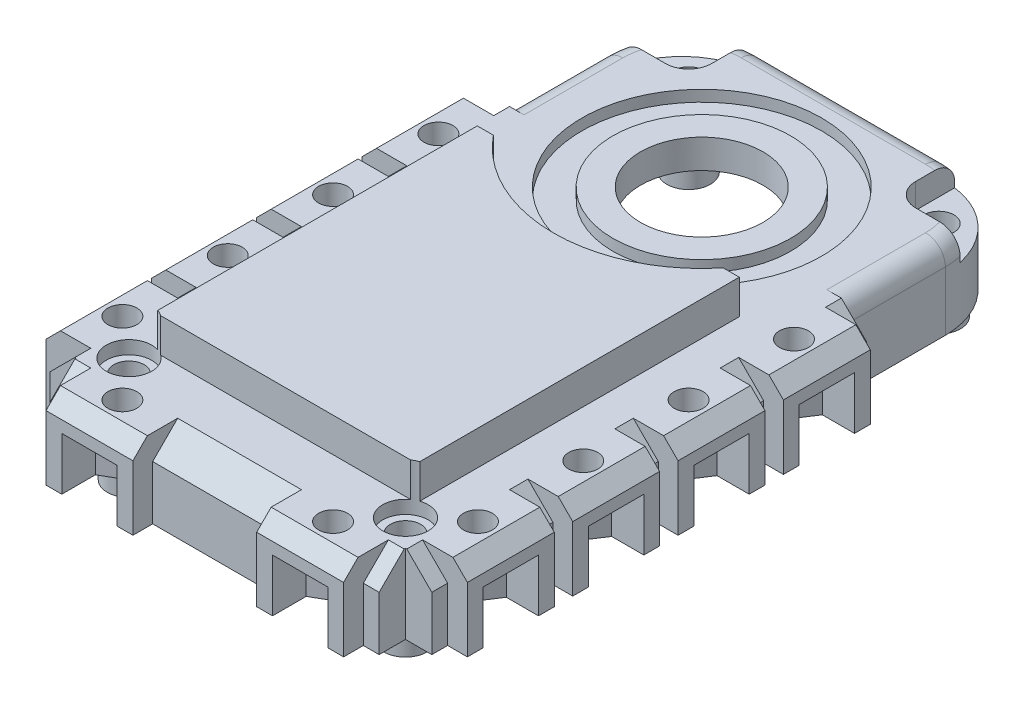
SolidWorks part; units mm, degrees
ref_plane "Front Plane" through (0, 0, 0) normal (0, 0, 1) x (1, 0, 0)
ref_plane "Top Plane" through (0, 0, 0) normal (0, 1, 0) x (1, 0, 0)
ref_plane "Right Plane" through (0, 0, 0) normal (1, 0, 0) x (0, 0, -1)
sketch "Sketch1" plane through (0, 0, 0) normal (0, 1, 0) x (1, 0, 0)
  line L0 (-55, 0) -> (55, 0) construction
  line L1 (-16, -25) -> (16, -25)
  line L2 (-16, -25) -> (-16, 25)
  line L3 (-16, 25) -> (16, 25)
  line L4 (16, -25) -> (16, 25)
  line L5 (0, -55) -> (0, 55) construction
  point P4 (16, 0)
  point P9 (0, 25)
  dimension "D1" = 32
  dimension "D2" = 50
extrude "Boss-Extrude1" add sketch "Sketch1" along normal mid plane 6
sketch "Sketch4" plane through (0, 3, 0) normal (0, 1, 0) x (1, 0, 0)
  line L0 (-13, 19) -> (-13, 11.5)
  line L1 (-13, 11.5) -> (-14.5, 11.5)
  line L2 (-14.5, 11.5) -> (-14.5, 10.3)
  line L3 (-14.5, 10.3) -> (-16, 10.3)
  line L4 (-16, 25) -> (-16, -25)
  line L5 (-16, -25) -> (16, -25)
  line L6 (16, -25) -> (16, 25)
  line L7 (16, 25) -> (-16, 25)
  line L8 (-16, 10.3) -> (-16, 3.7)
  line L9 (-11.3, -25) -> (-4.7, -25)
  line L12 (-16, 3.7) -> (-14.5, 3.7)
  line L13 (-14.5, 3.7) -> (-14.5, 2.3)
  line L14 (-14.5, 2.3) -> (-16, 2.3)
  line L15 (-16, 2.3) -> (-16, -4.3)
  line L16 (-16, -5.7) -> (-16, -12.3)
  line L17 (-16, -4.3) -> (-14.5, -4.3)
  line L19 (-16, -5.7) -> (-14.5, -5.7)
  line L20 (-14.5, -4.3) -> (-14.5, -5.7)
  line L21 (-16, 25) -> (-16, -25) construction
  line L22 (-16, -13.7) -> (-16, -20.3)
  line L23 (-16, -12.3) -> (-14.5, -12.3)
  line L25 (-16, -13.7) -> (-14.5, -13.7)
  line L26 (-14.5, -12.3) -> (-14.5, -13.7)
  line L27 (-16, -20.3) -> (-14.5, -20.3)
  line L28 (-14.5, -20.3) -> (-14.5, -21.5)
  line L29 (-14.5, -21.5) -> (-12.5, -21.5)
  line L30 (-12.5, -21.5) -> (-12.5, -23.5)
  line L31 (-12.5, -23.5) -> (-11.3, -23.5)
  line L32 (-11.3, -23.5) -> (-11.3, -25)
  line L35 (-4.7, -23.5) -> (-4.7, -25)
  line L38 (0, -55) -> (0, 55) construction
  line L41 (-20, 25) -> (-20, -26)
  line L42 (-20, -26) -> (0, -26)
  line L43 (0, -23.5) -> (0, -26)
  line L44 (-4.7, -23.5) -> (0, -23.5)
  line L45 (16, 25) -> (-16, 25) construction
  line L46 (-20, 25) -> (-7, 25)
  arc A0 (-7, 25) -> (-13, 19) centre (-7, 19) ccw
  dimension "D6" = 6
  dimension "D2" = 6.6
  dimension "D3" = 1.2
  dimension "D4" = 1.4
  dimension "D5" = 1.5
  dimension "D7" = 1.5
  dimension "D8" = 4.7
  dimension "D9" = 13
  dimension "D10" = 20
  dimension "D11" = 13.5
  dimension "D12" = 51
  dimension "D1" = 0
extrude "Cut-Extrude1" cut sketch "Sketch4" against normal blind 10
mirror "Mirror1" about plane through (0, 0, 0) normal (1, 0, 0) of "Cut-Extrude1"
sketch "Sketch5" plane through (0, 3, 0) normal (0, 1, 0) x (1, 0, 0)
  line L0 (-16, 10.3) -> (-16, 3.7) construction
  line L1 (-14.5, 3.7) -> (-16, 3.7) construction
  line L2 (-11.3, -25) -> (-4.7, -25) construction
  line L3 (0, -55) -> (0, 55) construction
  circle A0 centre (-13.5, 7) radius 1.1
  circle A1 centre (13.5, 7) radius 1.1
  circle A2 centre (13.5, -1) radius 1.1
  circle A3 centre (13.5, -9) radius 1.1
  circle A4 centre (13.5, -17) radius 1.1
  circle A5 centre (-13.5, -1) radius 1.1
  circle A6 centre (-13.5, -9) radius 1.1
  circle A7 centre (-13.5, -17) radius 1.1
  circle A8 centre (-8, -22.5) radius 1.1
  circle A9 centre (8, -22.5) radius 1.1
  dimension "D3" = 2.2
  dimension "D1" = 2.5
  dimension "D2" = 3.3
  dimension "D6" = 8
  dimension "D7" = 27
  dimension "D8" = 16
  dimension "D9" = 2.5
  dimension "D10" = 8
  dimension "D4" = 2
  dimension "D5" = 4
extrude "Cut-Extrude2" cut sketch "Sketch5" against normal blind 10
chamfer "Chamfer1" distance 1.1 angle 45 10 edges at (8, 3, 25) (16, 3, -7) (16, 3, 1) (16, 3, 9) (16, 3, 17) (-8, 3, 25) (-16, 3, 17) (-16, 3, 9) (-16, 3, 1) (-16, 3, -7)
fillet "Fillet1" radius 1.5 5 edges at (13, 3, -15.25) (11.2426, 3, -23.2426) (0, 3, -25) (-11.2426, 3, -23.2426) (-13, 3, -15.25)
chamfer "Chamfer2" distance 1.9 angle 45 13 edges at (-14.5, 3, -3) (-14.5, 3, 13) (-14.5, 3, 5) (-14.5, 3, -10.9) (14.5, 3, -10.9) (14.5, 3, -3) (14.5, 3, 5) (14.5, 3, 13) (11.9, 3, 23.5) (0, 3, 23.5) (-11.9, 3, 23.5) (14.5, 3, 20.9) (-14.5, 3, 20.9)
sketch "Sketch24" plane through (0, 3, 0) normal (0, 1, 0) x (1, 0, 0)
  line L0 (-7, 25) -> (7, 25) construction
  circle A0 centre (0, 13.5) radius 9.1
  point P2 (0, 0)
  dimension "D1" = 18.2
  dimension "D2" = 11.5
extrude "Cut-Extrude15" cut sketch "Sketch24" against normal blind 0.85
sketch "Sketch8" plane through (0, 3, 0) normal (0, 1, 0) x (1, 0, 0)
  line L0 (0, -3.3) -> (0, 3.3) construction
  line L1 (-7, 25) -> (7, 25) construction
  circle A0 centre (0, 13.5) radius 6.75
  dimension "D1" = 13.5
  dimension "D2" = 11.5
extrude "Boss-Extrude3" add sketch "Sketch8" against normal up to surface (0.85 mm away) up to face at (0, 2.15, -4.4)
ref_plane "Plane1" through (0, 1, 0) normal (0, 1, 0) x (1, 0, 0)
sketch "Sketch12" plane through (0, 1, 0) normal (0, 1, 0) x (1, 0, 0)
  line L1 (-12.2876, 9.1) -> (-14.7124, 9.1)
  line L2 (-14.7124, 9.1) -> (-15.9249, 7) construction
  line L3 (-15.9249, 7) -> (-14.7124, 4.9) construction
  line L4 (-14.7124, 4.9) -> (-12.2876, 4.9)
  line L5 (-12.2876, 4.9) -> (-11.0751, 7)
  line L6 (-11.0751, 7) -> (-12.2876, 9.1)
  line L49 (-14.7124, 9.1) -> (-17.7124, 9.1)
  line L50 (-14.7124, 9.1) -> (-14.7124, 4.9) construction
  line L51 (-14.7124, 4.9) -> (-17.7124, 4.9)
  line L52 (-17.7124, 9.1) -> (-17.7124, 4.9)
  circle A0 centre (-13.5, 7) radius 2.1 construction
  circle A1 centre (-13.5, 7) radius 1.1 construction
  dimension "D1" = 4.2
  dimension "D2" = 3
extrude "Cut-Extrude7" cut sketch "Sketch12" against normal blind 1.5
sketch "Sketch13" plane through (0, -3, 0) normal (0, -1, 0) x (1, 0, 0)
  line L0 (-16, -4.9) -> (-13.4423, -4.9)
  line L1 (-13.4423, -4.9) -> (-12.5474, -6.45)
  line L2 (-16, -9.1) -> (-13.5577, -9.1)
  line L3 (-13.5577, -9.1) -> (-12.579, -7.6015)
  line L4 (-16, -4.9) -> (-16, -9.1)
  line L5 (-16, -4.9) -> (-12.2876, -4.9) construction
  line L6 (-16, -9.1) -> (-16, -4.9) construction
  line L7 (-12.2876, -4.9) -> (-11.0751, -7) construction
  circle A0 centre (-13.5, -7) radius 1.1 construction
  arc A1 (-12.579, -7.6015) -> (-12.5474, -6.45) centre (-13.5, -7) ccw
  point P8 (-16, -7)
extrude "Cut-Extrude8" cut sketch "Sketch13" against normal up to next
pattern_linear "LPattern1" count 4 spacing 8 along (0, 0, 1) of "Cut-Extrude7", "Cut-Extrude8"
sketch "Sketch14" plane through (0, 1, 0) normal (0, 1, 0) x (1, 0, 0)
  line L1 (-8, -24.9249) -> (-5.9, -23.7124) construction
  line L2 (-5.9, -23.7124) -> (-5.9, -21.2876)
  line L3 (-5.9, -21.2876) -> (-8, -20.0751)
  line L4 (-8, -20.0751) -> (-10.1, -21.2876)
  line L5 (-10.1, -21.2876) -> (-10.1, -23.7124)
  line L6 (-10.1, -23.7124) -> (-8, -24.9249) construction
  line L7 (-10.1, -23.7124) -> (-5.9, -23.7124) construction
  line L8 (-10.1, -23.7124) -> (-10.1, -26.7124)
  line L9 (-10.1, -26.7124) -> (-5.9, -26.7124)
  line L10 (-5.9, -23.7124) -> (-5.9, -26.7124)
  circle A0 centre (-8, -22.5) radius 2.1 construction
  circle A1 centre (-8, -22.5) radius 1.1 construction
  dimension "D1" = 4.2
  dimension "D2" = 3
extrude "Cut-Extrude9" cut sketch "Sketch14" against normal blind 1.55
sketch "Sketch15" plane through (0, -3, 0) normal (0, -1, 0) x (1, 0, 0)
  line L0 (-10.1, 25) -> (-5.9, 25)
  line L1 (-5.9, 25) -> (-5.9, 22.4423)
  line L2 (-5.9, 22.4423) -> (-7.45, 21.5474)
  line L3 (-10.1, 25) -> (-10.1, 22.4423)
  line L4 (-10.1, 22.4423) -> (-8.55, 21.5474)
  line L5 (-5.9, 25) -> (-5.9, 21.2876) construction
  line L6 (-5.9, 21.2876) -> (-8, 20.0751) construction
  line L8 (-11.3, 25) -> (-4.7, 25) construction
  circle A0 centre (-8, 22.5) radius 1.1 construction
  arc A1 (-8.55, 21.5474) -> (-7.45, 21.5474) centre (-8, 22.5) ccw
  point P7 (-8, 25)
extrude "Cut-Extrude10" cut sketch "Sketch15" against normal up to next
mirror "Mirror2" about plane through (0, 0, 0) normal (1, 0, 0) of "Cut-Extrude8", "LPattern1", "Cut-Extrude9", "Cut-Extrude10", "Cut-Extrude7"
sketch "Sketch16" plane through (0, -3, 0) normal (0, -1, 0) x (1, 0, 0)
  line L0 (7, -25) -> (-7, -25) construction
  line L1 (-11.74, 19.1) -> (11.74, 19.1)
  line L2 (-11.74, 19.1) -> (-11.74, -17.74)
  line L3 (-5.74, -23.74) -> (5.74, -23.74)
  line L4 (11.74, 19.1) -> (11.74, -17.74)
  line L5 (-13, -19) -> (-13, -11.5) construction
  line L6 (-4.7, 23.5) -> (4.7, 23.5) construction
  arc A0 (11.74, -17.74) -> (5.74, -23.74) centre (5.74, -17.74) cw
  arc A1 (-5.74, -23.74) -> (-11.74, -17.74) centre (-5.74, -17.74) cw
  arc A2 (7, -25) -> (13, -19) centre (7, -19) ccw construction
  point P11 (0, -23.74)
  dimension "D1" = 1.26
  dimension "D2" = 1.26
  dimension "D3" = 4.4
extrude "Cut-Extrude11" cut sketch "Sketch16" against normal blind 3.8
sketch "Sketch17" plane through (0, 0.8, 0) normal (0, -1, 0) x (1, 0, 0)
  line L1 (7, -25) -> (-7, -25) construction
  circle A2 centre (0, -13.5) radius 4.65
  point P2 (0, 0)
  dimension "D1" = 11.5
  dimension "D2" = 9.3
sketch "Sketch22" plane through (0, 0.8, 0) normal (0, -1, 0) x (1, 0, 0)
  line L0 (7, -25) -> (-7, -25) construction
  line L1 (-10.5, 19.5) -> (10.5, 19.5) construction
  line L3 (-9.5, -22) -> (9.5, -22) construction
  circle A0 centre (-10.5, 19.5) radius 1.65
  circle A1 centre (10.5, 19.5) radius 1.65
  circle A2 centre (9.5, -22) radius 1.65
  circle A3 centre (-9.5, -22) radius 1.65
  point P8 (0, -22)
  point P10 (0, 19.5)
  dimension "D5" = 3.3
  dimension "D1" = 21
  dimension "D2" = 19
  dimension "D3" = 3
  dimension "D4" = 41.5
extrude "Boss-Extrude7" add sketch "Sketch22" along normal offset from surface (5.8 mm away) 2 up to face at (0, -3, -7.8742) offset beyond the face yes
sketch "Sketch23" plane through (0, -5, 0) normal (0, -1, 0) x (1, 0, 0)
  circle A0 centre (10.5, 19.5) radius 1.15
  circle A1 centre (-10.5, 19.5) radius 1.15
  circle A2 centre (9.5, -22) radius 1.15
  circle A3 centre (-9.5, -22) radius 1.15
  circle A4 centre (-9.5, -22) radius 1.65 construction
  arc A5 (10.7931, -20.9751) -> (8.3225, -23.1558) centre (9.5, -22) ccw construction
  circle A6 centre (-10.5, 19.5) radius 1.65 construction
  circle A7 centre (10.5, 19.5) radius 1.65 construction
  dimension "D1" = 2.3
extrude "Cut-Extrude13" cut sketch "Sketch23" against normal through all
extrude "Cut-Extrude14" cut sketch "Sketch17" against normal blind 10
sketch "Sketch25" plane through (0, 3, 0) normal (0, 1, 0) x (1, 0, 0)
  line L0 (-7, 25) -> (7, 25) construction
  line L1 (-9.95, 6.4) -> (-8.7265, 6.4)
  line L2 (-9.95, 6.4) -> (-9.95, -18.1)
  line L3 (-9.95, -18.1) -> (9.95, -18.1)
  line L4 (9.95, 6.4) -> (9.95, -18.1)
  line L5 (8.7265, 6.4) -> (9.95, 6.4)
  arc A0 (-8.7265, 6.4) -> (8.7265, 6.4) centre (0, 13.5) ccw
  circle A1 centre (0, 13.5) radius 4.65 construction
  point P4 (0, 0)
  dimension "D4" = 22.5
  dimension "D1" = 19.9
  dimension "D2" = 24.5
  dimension "D3" = 18.6
extrude "Boss-Extrude8" add sketch "Sketch25" along normal blind 2.6
sketch "Sketch26" plane through (0, 3, 0) normal (0, 1, 0) x (1, 0, 0)
  line L0 (-7.75, 24.9529) -> (-7.75, 22)
  line L1 (-9.5, 20.25) -> (-12.8683, 20.25)
  line L2 (-13, 11.5) -> (-13, 19) construction
  line L3 (-7, 25) -> (7, 25) construction
  arc A0 (-9.5, 20.25) -> (-7.75, 22) centre (-9.5, 22) ccw
  arc A1 (-7, 25) -> (-13, 19) centre (-7, 19) ccw construction
  arc A2 (-10.6074, 21.69) -> (-8.9954, 23.0334) centre (-9.5, 22) ccw construction
  arc A3 (-7.75, 24.9529) -> (-12.8683, 20.25) centre (-7, 19) ccw
  dimension "D1" = 5.25
  dimension "D2" = 4.75
extrude "Cut-Extrude16" cut sketch "Sketch26" against normal blind 1.9
sketch "Sketch27" plane through (0, 5.6, 0) normal (0, 1, 0) x (1, 0, 0)
  circle A0 centre (-10.5, -19.5) radius 1.725
  circle A1 centre (-10.5, -19.5) radius 1.15 construction
  dimension "D1" = 3.45
extrude "Cut-Extrude17" cut sketch "Sketch27" against normal offset from surface (3.6 mm away) 1 up to face at (-0.2866, 3, 3.5156) offset beyond the face yes
mirror "Mirror3" about plane through (0, 0, 0) normal (1, 0, 0) of "Cut-Extrude17", "Cut-Extrude16"
